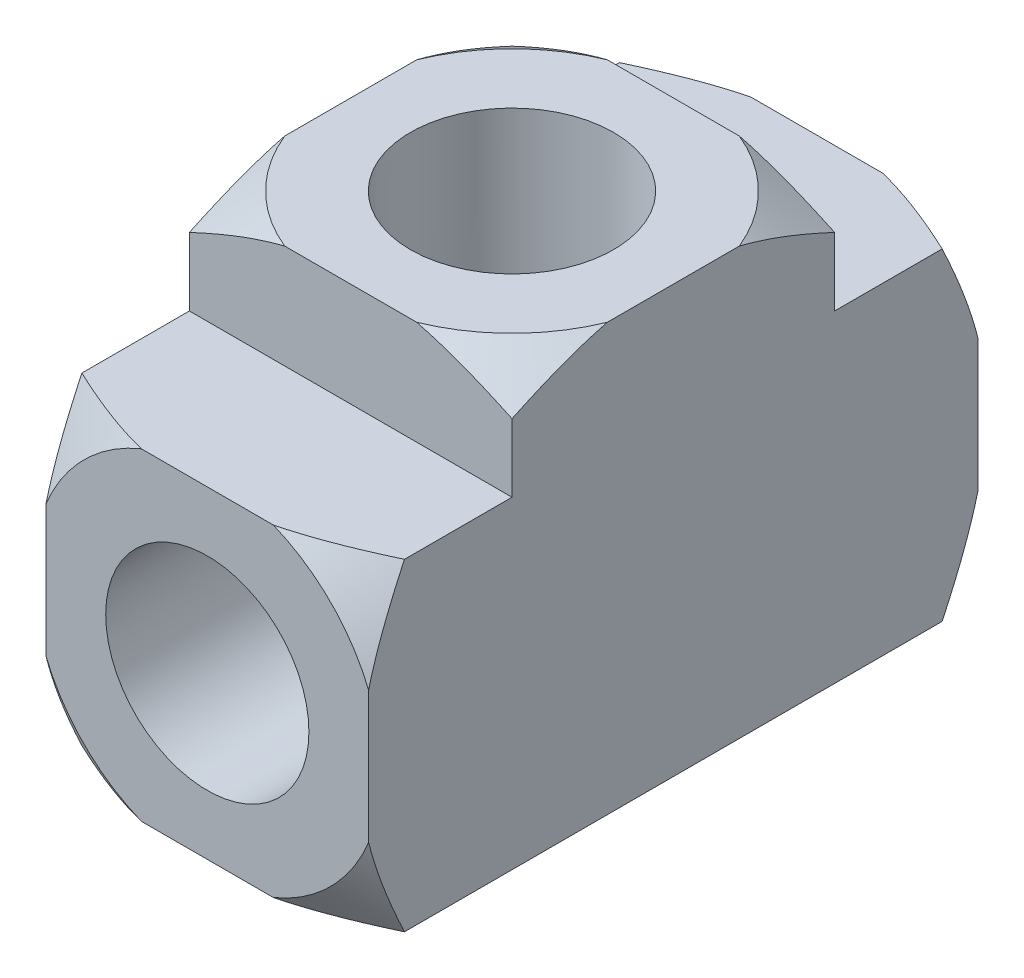
SolidWorks part; units mm, degrees
material "Brass"
ref_plane "Front Plane" through (0, 0, 0) normal (0, 0, 1) x (1, 0, 0)
ref_plane "Top Plane" through (0, 0, 0) normal (0, 1, 0) x (1, 0, 0)
ref_plane "Right Plane" through (0, 0, 0) normal (1, 0, 0) x (0, 0, -1)
sketch "Sketch1" plane through (0, 0, 0) normal (1, 0, 0) x (0, 0, -1)
  line L0 (-13.4937, -7.1438) -> (13.4938, -7.1437)
  line L1 (13.4938, -7.1437) -> (13.4937, 7.1438)
  line L2 (13.4937, 7.1438) -> (7.1437, 7.1438)
  line L3 (7.1437, 7.1438) -> (7.1437, 11.7437)
  line L4 (7.1437, 11.7437) -> (-7.1438, 11.7438)
  line L5 (-7.1438, 11.7438) -> (-7.1437, 7.1438)
  line L6 (-7.1437, 7.1438) -> (-13.4937, 7.1437)
  line L7 (-13.4937, 7.1437) -> (-13.4937, -7.1438)
  line L8 (-13.4937, 7.1437) -> (13.4938, -7.1437) construction
  line L9 (13.4937, 7.1438) -> (-13.4937, -7.1438) construction
  line L10 (0, 0) -> (0, 11.7438) construction
  dimension "D1" = 26.9875
  dimension "D2" = 14.2875
  dimension "D3" = 4.6
extrude "Boss-Extrude1" add sketch "Sketch1" along normal mid plane 14.2875
sketch "Sketch2" plane through (0, 0, 13.4937) normal (0, 0, 1) x (1, 0, 0)
  circle A0 centre (0, 0) radius 4.5
  dimension "D1" = 9
extrude "Cut-Extrude1" cut sketch "Sketch2" against normal through all
sketch "Sketch3" plane through (0, 11.7438, 0) normal (0, 1, 0) x (1, 0, 0)
  circle A0 centre (0, 0) radius 4.5
  dimension "D1" = 9
extrude "Cut-Extrude2" cut sketch "Sketch3" against normal up to next
ref_axis "Longitudinal" through (0, 0, -13.4938) along (0, 0, 1)
ref_axis "Longitudinal B" through (0, 0, 0) along (0, 1, 0)
ref_plane "Diagonal A" through (0, 0, 0) normal (0.7071, 0.7071, 0) x (0, 0, -1)
sketch "Sketch4" plane through (0, 0, 0) normal (0.7071, 0.7071, 0) x (0, 0, -1)
  line L0 (13.4937, 10.1028) -> (13.9937, 6.9674)
  line L2 (13.9937, 6.9674) -> (11.9062, 10.1028)
  line L4 (11.9062, 10.1028) -> (13.4937, 10.1028)
  line L5 (13.4937, 0) -> (13.4937, 10.1028) construction
  line L6 (0, -10.1028) -> (0, 13.3555) construction
  line L7 (-13.4937, -10.1028) -> (13.4938, -10.1028) construction
  line L8 (7.1437, 13.3555) -> (-7.1438, 13.3555) construction
  line L9 (-13.4937, 10.1028) -> (-13.9937, 6.9674)
  line L10 (-11.9062, 10.1028) -> (-13.4937, 10.1028)
  line L11 (-13.9937, 6.9674) -> (-11.9062, 10.1028)
  dimension "D1" = 1.5875
  dimension "D2" = 3.175
  dimension "D3" = 0.5
revolve "Cut-Revolve1" cut sketch "Sketch4" angle 360 about axis through (0, 0, -13.4938) along (0, 0, 1)
ref_plane "Diagonal B" through (0, 0, 0) normal (0.7071, 0, -0.7071) x (-0.7071, 0, -0.7071)
sketch "Sketch5" plane through (0, 0, 0) normal (0.7071, 0, -0.7071) x (-0.7071, 0, -0.7071)
  line L0 (10.1028, 11.7437) -> (6.9674, 12.2437)
  line L1 (6.9674, 12.2437) -> (10.1028, 10.1562)
  line L3 (10.1028, 7.1437) -> (10.1028, 11.7437) construction
  line L5 (10.1028, 10.1562) -> (10.1028, 11.7437)
  line L6 (0, 11.7437) -> (10.1028, 11.7437) construction
  dimension "D1" = 1.5875
  dimension "D2" = 3.175
  dimension "D3" = 0.5
revolve "Cut-Revolve2" cut sketch "Sketch5" angle 360 about axis through (0, 0, 0) along (0, 1, 0)
